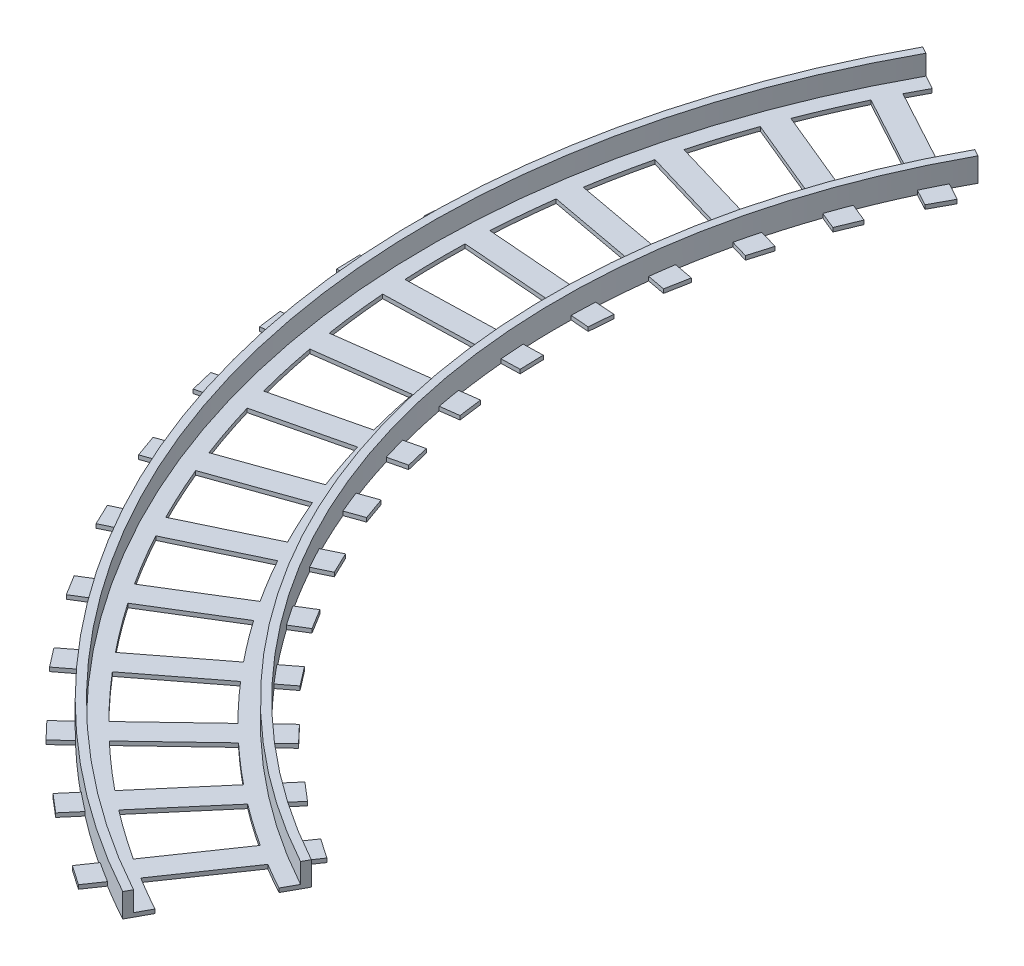
SolidWorks part; units mm, degrees
ref_plane "Front Plane" through (0, 0, 0) normal (0, 0, 1) x (1, 0, 0)
ref_plane "Top Plane" through (0, 0, 0) normal (0, 1, 0) x (1, 0, 0)
ref_plane "Right Plane" through (0, 0, 0) normal (1, 0, 0) x (0, 0, -1)
sketch "Sketch1" plane through (0, 0, 0) normal (0, 1, 0) x (1, 0, 0)
  arc A0 (-184.2454, 100.7652) -> (-100.7652, -184.2454) centre (0, 0) ccw
  arc A1 (-153.5378, 83.971) -> (-83.971, -153.5378) centre (0, 0) ccw
  dimension "D1" = 35
  dimension "D2" = 210
ref_plane "Plane1" through (0, 0, 0) normal (0, 1, 0) x (1, 0, 0)
ref_plane "Plane3" through (0, 0, 0) normal (-0.4798, 0, 0.8774) x (0.8774, 0, 0.4798)
sketch "Sketch2" plane through (0, 0, 0) normal (-0.4798, 0, 0.8774) x (0.8774, 0, 0.4798)
  line L0 (0, 0) -> (-210, 0) construction
  line L2 (-210, 0) -> (-210, 6)
  line L3 (-210, 6) -> (-208, 6)
  line L4 (-208, 1) -> (-208, 6)
  line L6 (-175, 0) -> (-175, 6)
  line L7 (-175, 6) -> (-177, 6)
  line L8 (-177, 1) -> (-177, 6)
  line L9 (-208, 1) -> (-204, 1)
  line L10 (-175, 0) -> (-181, 0)
  line L11 (-210, 0) -> (-204, 0)
  line L12 (-204, 1) -> (-204, 0)
  line L14 (-177, 1) -> (-181, 1)
  line L15 (-181, 0) -> (-181, 1)
sweep "Sweep1" add profiles "Sketch2" path "Sketch1"
sketch "Sketch3" plane through (0, 0, 0) normal (0, 1, 0) x (1, 0, 0)
  line L0 (-200.4806, 77.7925) -> (-158.8924, 60.6047)
  line L1 (-188.9138, 92.706) -> (-200.2068, 65.3811) construction
  line L2 (-163.5804, 67.6052) -> (-154.5226, 89.5218) construction
  line L3 (-184.3356, 100.8145) -> (-153.5429, 83.9738) construction
  line L4 (-16.8892, 9.2368) -> (16.8892, -9.2368) construction
  line L5 (-100.7652, -184.2454) -> (-83.971, -153.5378) construction
  line L6 (-202.7723, 72.2474) -> (-161.1841, 55.0596)
  line L7 (-202.7723, 72.2474) -> (-200.4806, 77.7925)
  line L8 (-161.1841, 55.0596) -> (-158.8924, 60.6047)
  line L9 (-191.2508, 98.3223) -> (-151.687, 76.8815)
  line L10 (-194.1096, 93.0471) -> (-154.5458, 71.6063)
  line L11 (-194.1096, 93.0471) -> (-191.2508, 98.3223)
  line L12 (-154.5458, 71.6063) -> (-151.687, 76.8815)
  line L193 (-117.7748, -179.9257) -> (-92.316, -142.8198)
  line L194 (-112.8274, -183.3202) -> (-87.3685, -146.2143)
  line L195 (-112.8274, -183.3202) -> (-117.7748, -179.9257)
  line L196 (-87.3685, -146.2143) -> (-92.316, -142.8198)
  line L197 (-135.937, -166.6292) -> (-106.739, -132.3877)
  line L198 (-131.3714, -170.5223) -> (-102.1734, -136.2808)
  line L199 (-131.3714, -170.5223) -> (-135.937, -166.6292)
  line L200 (-102.1734, -136.2808) -> (-106.739, -132.3877)
  line L201 (-152.6098, -151.5071) -> (-119.9925, -120.5052)
  line L202 (-148.4762, -155.8561) -> (-115.859, -124.8542)
  line L203 (-148.4762, -155.8561) -> (-152.6098, -151.5071)
  line L204 (-115.859, -124.8542) -> (-119.9925, -120.5052)
  line L205 (-167.6106, -134.7251) -> (-131.9314, -107.3025)
  line L206 (-163.9542, -139.4823) -> (-128.2751, -112.0597)
  line L207 (-163.9542, -139.4823) -> (-167.6106, -134.7251)
  line L208 (-128.2751, -112.0597) -> (-131.9314, -107.3025)
  line L209 (-180.775, -116.4669) -> (-142.4249, -92.9241)
  line L210 (-177.6359, -121.5803) -> (-139.2858, -98.0374)
  line L211 (-177.6359, -121.5803) -> (-180.775, -116.4669)
  line L212 (-139.2858, -98.0374) -> (-142.4249, -92.9241)
  line L213 (-191.9588, -96.9328) -> (-151.3578, -77.5276)
  line L214 (-189.3714, -102.3462) -> (-148.7705, -82.941)
  line L215 (-189.3714, -102.3462) -> (-191.9588, -96.9328)
  line L216 (-148.7705, -82.941) -> (-151.3578, -77.5276)
  line L217 (-201.0395, -76.3366) -> (-158.6325, -61.2817)
  line L218 (-199.0321, -81.9909) -> (-156.6252, -66.9359)
  line L219 (-199.0321, -81.9909) -> (-201.0395, -76.3366)
  line L220 (-156.6252, -66.9359) -> (-158.6325, -61.2817)
  line L221 (-207.9175, -54.9041) -> (-164.1692, -44.3643)
  line L222 (-206.5122, -60.7372) -> (-162.7639, -50.1974)
  line L223 (-206.5122, -60.7372) -> (-207.9175, -54.9041)
  line L224 (-162.7639, -50.1974) -> (-164.1692, -44.3643)
  line L225 (-212.5175, -32.87) -> (-167.9072, -26.9609)
  line L226 (-211.7297, -38.8181) -> (-167.1193, -32.909)
  line L227 (-211.7297, -38.8181) -> (-212.5175, -32.87)
  line L228 (-167.1193, -32.909) -> (-167.9072, -26.9609)
  line L229 (-214.7892, -10.4758) -> (-169.8056, -9.2622)
  line L230 (-214.6274, -16.4736) -> (-169.6438, -15.26)
  line L231 (-214.6274, -16.4736) -> (-214.7892, -10.4758)
  line L232 (-169.6438, -15.26) -> (-169.8056, -9.2622)
  line L233 (-214.7076, 12.0331) -> (-169.8435, 8.5381)
  line L234 (-215.1736, 6.0513) -> (-170.3095, 2.5562)
  line L235 (-215.1736, 6.0513) -> (-214.7076, 12.0331)
  line L236 (-170.3095, 2.5562) -> (-169.8435, 8.5381)
  line L237 (-212.2736, 34.4103) -> (-168.0206, 26.2448)
  line L238 (-213.3623, 28.5099) -> (-169.1094, 20.3444)
  line L239 (-213.3623, 28.5099) -> (-212.2736, 34.4103)
  line L240 (-169.1094, 20.3444) -> (-168.0206, 26.2448)
  line L241 (-207.5139, 56.4104) -> (-164.3569, 43.664)
  line L242 (-209.2134, 50.6561) -> (-166.0564, 37.9097)
  line L243 (-209.2134, 50.6561) -> (-207.5139, 56.4104)
  line L244 (-166.0564, 37.9097) -> (-164.3569, 43.664)
  line L245 (-183.3202, 112.8274) -> (-179.9257, 117.7748) [skipped]
  line L246 (-179.9257, 117.7748) -> (-142.8198, 92.316) [skipped]
  line L247 (-183.3202, 112.8274) -> (-146.2143, 87.3685) [skipped]
  line L248 (-146.2143, 87.3685) -> (-142.8198, 92.316) [skipped]
  line L249 (-166.6292, 135.937) -> (-132.3877, 106.739) [skipped]
  line L250 (-170.5223, 131.3714) -> (-136.2808, 102.1734) [skipped]
  line L251 (-170.5223, 131.3714) -> (-166.6292, 135.937) [skipped]
  line L252 (-136.2808, 102.1734) -> (-132.3877, 106.739) [skipped]
  line L253 (-151.5071, 152.6098) -> (-120.5052, 119.9925) [skipped]
  line L254 (-155.8561, 148.4762) -> (-124.8542, 115.859) [skipped]
  line L255 (-155.8561, 148.4762) -> (-151.5071, 152.6098) [skipped]
  line L256 (-124.8542, 115.859) -> (-120.5052, 119.9925) [skipped]
  line L257 (-139.4823, 163.9542) -> (-112.0597, 128.2751) [skipped]
  line L258 (-112.0597, 128.2751) -> (-107.3025, 131.9314) [skipped]
  line L259 (-134.7251, 167.6106) -> (-107.3025, 131.9314) [skipped]
  line L260 (-139.4823, 163.9542) -> (-134.7251, 167.6106) [skipped]
  line L261 (-116.4669, 180.775) -> (-92.9241, 142.4249) [skipped]
  line L262 (-121.5803, 177.6359) -> (-98.0374, 139.2858) [skipped]
  line L263 (-121.5803, 177.6359) -> (-116.4669, 180.775) [skipped]
  line L264 (-98.0374, 139.2858) -> (-92.9241, 142.4249) [skipped]
  line L265 (-96.9328, 191.9588) -> (-77.5276, 151.3578) [skipped]
  line L266 (-102.3462, 189.3714) -> (-82.941, 148.7705) [skipped]
  line L267 (-102.3462, 189.3714) -> (-96.9328, 191.9588) [skipped]
  line L268 (-82.941, 148.7705) -> (-77.5276, 151.3578) [skipped]
  line L269 (-76.3366, 201.0395) -> (-61.2817, 158.6325) [skipped]
  line L270 (-81.9909, 199.0321) -> (-66.9359, 156.6252) [skipped]
  line L271 (-81.9909, 199.0321) -> (-76.3366, 201.0395) [skipped]
  line L272 (-66.9359, 156.6252) -> (-61.2817, 158.6325) [skipped]
  line L273 (-54.9041, 207.9175) -> (-44.3643, 164.1692) [skipped]
  line L274 (-60.7372, 206.5122) -> (-50.1974, 162.7639) [skipped]
  line L275 (-60.7372, 206.5122) -> (-54.9041, 207.9175) [skipped]
  line L276 (-50.1974, 162.7639) -> (-44.3643, 164.1692) [skipped]
  line L277 (-32.87, 212.5175) -> (-26.9609, 167.9072) [skipped]
  line L278 (-38.8181, 211.7297) -> (-32.909, 167.1193) [skipped]
  line L279 (-38.8181, 211.7297) -> (-32.87, 212.5175) [skipped]
  line L280 (-32.909, 167.1193) -> (-26.9609, 167.9072) [skipped]
  line L281 (-10.4758, 214.7892) -> (-9.2622, 169.8056) [skipped]
  line L282 (-16.4736, 214.6274) -> (-15.26, 169.6438) [skipped]
  line L283 (-16.4736, 214.6274) -> (-10.4758, 214.7892) [skipped]
  line L284 (-15.26, 169.6438) -> (-9.2622, 169.8056) [skipped]
  line L285 (12.0331, 214.7076) -> (8.5381, 169.8435) [skipped]
  line L286 (6.0513, 215.1736) -> (2.5562, 170.3095) [skipped]
  line L287 (6.0513, 215.1736) -> (12.0331, 214.7076) [skipped]
  line L288 (2.5562, 170.3095) -> (8.5381, 169.8435) [skipped]
  line L289 (34.4103, 212.2736) -> (26.2448, 168.0206) [skipped]
  line L290 (28.5099, 213.3623) -> (20.3444, 169.1094) [skipped]
  line L291 (28.5099, 213.3623) -> (34.4103, 212.2736) [skipped]
  line L292 (20.3444, 169.1094) -> (26.2448, 168.0206) [skipped]
  line L293 (56.4104, 207.5139) -> (43.664, 164.3569) [skipped]
  line L294 (50.6561, 209.2134) -> (37.9097, 166.0564) [skipped]
  line L295 (50.6561, 209.2134) -> (56.4104, 207.5139) [skipped]
  line L296 (37.9097, 166.0564) -> (43.664, 164.3569) [skipped]
  line L297 (55.0596, 161.1841) -> (60.6047, 158.8924) [skipped]
  line L298 (-71.6063, -154.5458) -> (-76.8815, -151.687) [skipped]
  line L299 (-98.3223, -191.2508) -> (-76.8815, -151.687) [skipped]
  line L300 (-93.0471, -194.1096) -> (-71.6063, -154.5458) [skipped]
  line L301 (-93.0471, -194.1096) -> (-98.3223, -191.2508) [skipped]
  line L302 (32.87, -212.5175) -> (26.9609, -167.9072) [skipped]
  line L303 (38.8181, -211.7297) -> (32.909, -167.1193) [skipped]
  line L304 (38.8181, -211.7297) -> (32.87, -212.5175) [skipped]
  line L305 (32.909, -167.1193) -> (26.9609, -167.9072) [skipped]
  line L306 (10.4758, -214.7892) -> (9.2622, -169.8056) [skipped]
  line L307 (16.4736, -214.6274) -> (15.26, -169.6438) [skipped]
  line L308 (16.4736, -214.6274) -> (10.4758, -214.7892) [skipped]
  line L309 (15.26, -169.6438) -> (9.2622, -169.8056) [skipped]
  line L310 (-12.0331, -214.7076) -> (-8.5381, -169.8435) [skipped]
  line L311 (-6.0513, -215.1736) -> (-2.5562, -170.3095) [skipped]
  line L312 (-6.0513, -215.1736) -> (-12.0331, -214.7076) [skipped]
  line L313 (-2.5562, -170.3095) -> (-8.5381, -169.8435) [skipped]
  line L314 (-34.4103, -212.2736) -> (-26.2448, -168.0206) [skipped]
  line L315 (-28.5099, -213.3623) -> (-20.3444, -169.1094) [skipped]
  line L316 (-28.5099, -213.3623) -> (-34.4103, -212.2736) [skipped]
  line L317 (-20.3444, -169.1094) -> (-26.2448, -168.0206) [skipped]
  line L318 (-56.4104, -207.5139) -> (-43.664, -164.3569) [skipped]
  line L319 (-50.6561, -209.2134) -> (-37.9097, -166.0564) [skipped]
  line L320 (-50.6561, -209.2134) -> (-56.4104, -207.5139) [skipped]
  line L321 (-37.9097, -166.0564) -> (-43.664, -164.3569) [skipped]
  line L322 (-72.2474, -202.7723) -> (-55.0596, -161.1841) [skipped]
  line L323 (-55.0596, -161.1841) -> (-60.6047, -158.8924) [skipped]
  line L324 (-77.7925, -200.4806) -> (-60.6047, -158.8924) [skipped]
  line L325 (-72.2474, -202.7723) -> (-77.7925, -200.4806) [skipped]
  line L326 (179.9257, -117.7748) -> (142.8198, -92.316) [skipped]
  line L327 (183.3202, -112.8274) -> (146.2143, -87.3685) [skipped]
  line L328 (183.3202, -112.8274) -> (179.9257, -117.7748) [skipped]
  line L329 (146.2143, -87.3685) -> (142.8198, -92.316) [skipped]
  line L330 (166.6292, -135.937) -> (132.3877, -106.739) [skipped]
  line L331 (170.5223, -131.3714) -> (136.2808, -102.1734) [skipped]
  line L332 (170.5223, -131.3714) -> (166.6292, -135.937) [skipped]
  line L333 (136.2808, -102.1734) -> (132.3877, -106.739) [skipped]
  line L334 (151.5071, -152.6098) -> (120.5052, -119.9925) [skipped]
  line L335 (155.8561, -148.4762) -> (124.8542, -115.859) [skipped]
  line L336 (155.8561, -148.4762) -> (151.5071, -152.6098) [skipped]
  line L337 (124.8542, -115.859) -> (120.5052, -119.9925) [skipped]
  line L338 (134.7251, -167.6106) -> (107.3025, -131.9314) [skipped]
  line L339 (139.4823, -163.9542) -> (112.0597, -128.2751) [skipped]
  line L340 (139.4823, -163.9542) -> (134.7251, -167.6106) [skipped]
  line L341 (112.0597, -128.2751) -> (107.3025, -131.9314) [skipped]
  line L342 (116.4669, -180.775) -> (92.9241, -142.4249) [skipped]
  line L343 (121.5803, -177.6359) -> (98.0374, -139.2858) [skipped]
  line L344 (121.5803, -177.6359) -> (116.4669, -180.775) [skipped]
  line L345 (98.0374, -139.2858) -> (92.9241, -142.4249) [skipped]
  line L346 (96.9328, -191.9588) -> (77.5276, -151.3578) [skipped]
  line L347 (102.3462, -189.3714) -> (82.941, -148.7705) [skipped]
  line L348 (102.3462, -189.3714) -> (96.9328, -191.9588) [skipped]
  line L349 (82.941, -148.7705) -> (77.5276, -151.3578) [skipped]
  line L350 (76.3366, -201.0395) -> (61.2817, -158.6325) [skipped]
  line L351 (81.9909, -199.0321) -> (66.9359, -156.6252) [skipped]
  line L352 (81.9909, -199.0321) -> (76.3366, -201.0395) [skipped]
  line L353 (66.9359, -156.6252) -> (61.2817, -158.6325) [skipped]
  line L354 (54.9041, -207.9175) -> (44.3643, -164.1692) [skipped]
  line L355 (60.7372, -206.5122) -> (50.1974, -162.7639) [skipped]
  line L356 (60.7372, -206.5122) -> (54.9041, -207.9175) [skipped]
  line L357 (50.1974, -162.7639) -> (44.3643, -164.1692) [skipped]
  line L358 (77.7925, 200.4806) -> (60.6047, 158.8924) [skipped]
  line L359 (72.2474, 202.7723) -> (55.0596, 161.1841) [skipped]
  line L360 (72.2474, 202.7723) -> (77.7925, 200.4806) [skipped]
  line L361 (98.3223, 191.2508) -> (76.8815, 151.687) [skipped]
  line L362 (93.0471, 194.1096) -> (71.6063, 154.5458) [skipped]
  line L363 (93.0471, 194.1096) -> (98.3223, 191.2508) [skipped]
  line L364 (71.6063, 154.5458) -> (76.8815, 151.687) [skipped]
  line L365 (117.7748, 179.9257) -> (92.316, 142.8198) [skipped]
  line L366 (112.8274, 183.3202) -> (87.3685, 146.2143) [skipped]
  line L367 (112.8274, 183.3202) -> (117.7748, 179.9257) [skipped]
  line L368 (87.3685, 146.2143) -> (92.316, 142.8198) [skipped]
  line L369 (135.937, 166.6292) -> (106.739, 132.3877) [skipped]
  line L370 (131.3714, 170.5223) -> (102.1734, 136.2808) [skipped]
  line L371 (131.3714, 170.5223) -> (135.937, 166.6292) [skipped]
  line L372 (102.1734, 136.2808) -> (106.739, 132.3877) [skipped]
  line L373 (152.6098, 151.5071) -> (119.9925, 120.5052) [skipped]
  line L374 (148.4762, 155.8561) -> (115.859, 124.8542) [skipped]
  line L375 (148.4762, 155.8561) -> (152.6098, 151.5071) [skipped]
  line L376 (115.859, 124.8542) -> (119.9925, 120.5052) [skipped]
  line L377 (167.6106, 134.7251) -> (131.9314, 107.3025) [skipped]
  line L378 (163.9542, 139.4823) -> (128.2751, 112.0597) [skipped]
  line L379 (163.9542, 139.4823) -> (167.6106, 134.7251) [skipped]
  line L380 (128.2751, 112.0597) -> (131.9314, 107.3025) [skipped]
  line L381 (180.775, 116.4669) -> (142.4249, 92.9241) [skipped]
  line L382 (177.6359, 121.5803) -> (139.2858, 98.0374) [skipped]
  line L383 (177.6359, 121.5803) -> (180.775, 116.4669) [skipped]
  line L384 (139.2858, 98.0374) -> (142.4249, 92.9241) [skipped]
  line L385 (191.9588, 96.9328) -> (151.3578, 77.5276) [skipped]
  line L386 (189.3714, 102.3462) -> (148.7705, 82.941) [skipped]
  line L387 (189.3714, 102.3462) -> (191.9588, 96.9328) [skipped]
  line L388 (148.7705, 82.941) -> (151.3578, 77.5276) [skipped]
  line L389 (201.0395, 76.3366) -> (158.6325, 61.2817) [skipped]
  line L390 (199.0321, 81.9909) -> (156.6252, 66.9359) [skipped]
  line L391 (199.0321, 81.9909) -> (201.0395, 76.3366) [skipped]
  line L392 (156.6252, 66.9359) -> (158.6325, 61.2817) [skipped]
  line L393 (207.9175, 54.9041) -> (164.1692, 44.3643) [skipped]
  line L394 (206.5122, 60.7372) -> (162.7639, 50.1974) [skipped]
  line L395 (206.5122, 60.7372) -> (207.9175, 54.9041) [skipped]
  line L396 (162.7639, 50.1974) -> (164.1692, 44.3643) [skipped]
  line L397 (212.5175, 32.87) -> (167.9072, 26.9609) [skipped]
  line L398 (211.7297, 38.8181) -> (167.1193, 32.909) [skipped]
  line L399 (211.7297, 38.8181) -> (212.5175, 32.87) [skipped]
  line L400 (167.1193, 32.909) -> (167.9072, 26.9609) [skipped]
  line L401 (214.7892, 10.4758) -> (169.8056, 9.2622) [skipped]
  line L402 (214.6274, 16.4736) -> (169.6438, 15.26) [skipped]
  line L403 (214.6274, 16.4736) -> (214.7892, 10.4758) [skipped]
  line L404 (169.6438, 15.26) -> (169.8056, 9.2622) [skipped]
  line L405 (214.7076, -12.0331) -> (169.8435, -8.5381) [skipped]
  line L406 (215.1736, -6.0513) -> (170.3095, -2.5562) [skipped]
  line L407 (215.1736, -6.0513) -> (214.7076, -12.0331) [skipped]
  line L408 (170.3095, -2.5562) -> (169.8435, -8.5381) [skipped]
  line L409 (212.2736, -34.4103) -> (168.0206, -26.2448) [skipped]
  line L410 (213.3623, -28.5099) -> (169.1094, -20.3444) [skipped]
  line L411 (213.3623, -28.5099) -> (212.2736, -34.4103) [skipped]
  line L412 (169.1094, -20.3444) -> (168.0206, -26.2448) [skipped]
  line L413 (207.5139, -56.4104) -> (164.3569, -43.664) [skipped]
  line L414 (209.2134, -50.6561) -> (166.0564, -37.9097) [skipped]
  line L415 (209.2134, -50.6561) -> (207.5139, -56.4104) [skipped]
  line L416 (166.0564, -37.9097) -> (164.3569, -43.664) [skipped]
  line L417 (200.4806, -77.7925) -> (158.8924, -60.6047) [skipped]
  line L418 (202.7723, -72.2474) -> (161.1841, -55.0596) [skipped]
  line L419 (202.7723, -72.2474) -> (200.4806, -77.7925) [skipped]
  line L420 (161.1841, -55.0596) -> (158.8924, -60.6047) [skipped]
  line L421 (191.2508, -98.3223) -> (151.687, -76.8815) [skipped]
  line L422 (194.1096, -93.0471) -> (154.5458, -71.6063) [skipped]
  line L423 (194.1096, -93.0471) -> (191.2508, -98.3223) [skipped]
  line L424 (154.5458, -71.6063) -> (151.687, -76.8815) [skipped]
  arc A3 (-184.2454, 100.7652) -> (-100.7652, -184.2454) centre (0, 0) ccw construction
  arc A4 (-155.2926, 84.9307) -> (-84.9307, -155.2926) centre (0, 0) ccw construction
  point P19 (-87.6019, -171.4689)
  point P20 (-69.1986, -179.6865)
  point P21 (-50.0372, -185.9354)
  point P22 (-179.6865, 69.1986)
  point P25 (-161.3727, 105.0454)
  point P26 (-104.6955, 161.5999)
  point P27 (-121.0138, 149.771)
  point P30 (-171.4689, 87.6019)
  point P33 (-136.0062, 136.3012)
  point P34 (-149.5085, 121.338)
  point P35 (69.1986, 179.6865)
  point P36 (50.0372, 185.9354)
  point P37 (30.3275, 190.1471)
  point P38 (10.2856, 192.2756)
  point P39 (-9.869, 192.2974)
  point P40 (-29.9155, 190.2124)
  point P41 (-49.6342, 186.0434)
  point P42 (-68.8091, 179.836)
  point P43 (-87.2302, 171.6583)
  point P44 (-30.3275, -190.1471)
  point P45 (-10.2856, -192.2756)
  point P46 (9.869, -192.2974)
  point P47 (29.9155, -190.2124)
  point P48 (49.6342, -186.0434)
  point P49 (68.8091, -179.836)
  point P50 (87.2302, -171.6583)
  point P51 (104.6955, -161.5999)
  point P52 (121.0138, -149.771)
  point P53 (136.0062, -136.3012)
  point P54 (149.5085, -121.338)
  point P55 (161.3727, -105.0454)
  point P56 (171.4689, -87.6019)
  point P57 (179.6865, -69.1986)
  point P58 (185.9354, -50.0372)
  point P59 (190.1471, -30.3275)
  point P60 (192.2756, -10.2856)
  point P61 (192.2974, 9.869)
  point P62 (190.2124, 29.9155)
  point P63 (186.0434, 49.6342)
  point P64 (179.836, 68.8091)
  point P65 (171.6583, 87.2302)
  point P66 (161.5999, 104.6955)
  point P67 (149.771, 121.0138)
  point P68 (136.3012, 136.0062)
  point P69 (121.338, 149.5085)
  point P70 (105.0454, 161.3727)
  point P71 (87.6019, 171.4689)
  point P260 (-105.0454, -161.3727)
  point P265 (-121.338, -149.5085)
  point P270 (-136.3012, -136.0062)
  point P275 (-149.771, -121.0138)
  point P280 (-161.5999, -104.6955)
  point P285 (-171.6583, -87.2302)
  point P290 (-179.836, -68.8091)
  point P295 (-186.0434, -49.6342)
  point P300 (-190.2124, -29.9155)
  point P305 (-192.2974, -9.869)
  point P310 (-192.2756, 10.2856)
  point P315 (-190.1471, 30.3275)
  point P320 (-185.9354, 50.0372)
  point P323 (0, 0)
  dimension "D1" = 22.5
  dimension "D2" = 22.5
  dimension "D3" = 6
  dimension "D4" = 60
extrude "Boss-Extrude1" add sketch "Sketch3" along normal blind 1
